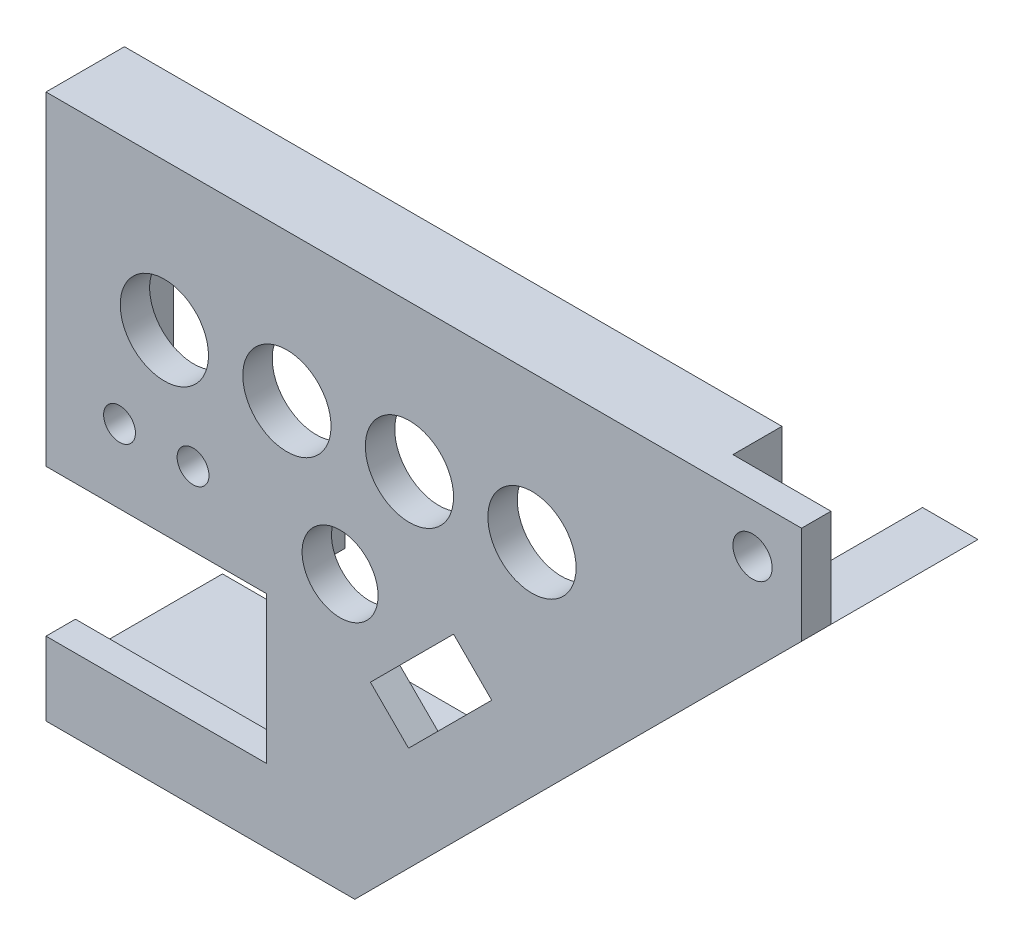
SolidWorks part; units mm, degrees
ref_plane "Plan de face" through (0, 0, 0) normal (0, 0, 1) x (1, 0, 0)
ref_plane "Plan de dessus" through (0, 0, 0) normal (0, 1, 0) x (1, 0, 0)
ref_plane "Plan de droite" through (0, 0, 0) normal (1, 0, 0) x (0, 0, -1)
sketch "Esquisse1" plane through (0, 0, 0) normal (0, 0, 1) x (1, 0, 0)
  line L0 (0, 0) -> (63, 0)
  line L1 (63, 0) -> (154.15, 91.15)
  line L2 (154.15, 91.15) -> (154.15, 111.15)
  line L3 (0, 111.15) -> (0, 0)
  line L4 (154.15, 111.15) -> (0, 111.15)
  dimension "D1" = 135
  dimension "D2" = 154.15
  dimension "D3" = 63
  dimension "D4" = 20
  dimension "D5" = 128.9056
extrude "Boss.-Extru.1" add sketch "Esquisse1" along normal blind 6
sketch "Esquisse2" plane through (0, 0, 6) normal (0, 0, 1) x (1, 0, 0)
  line L0 (0, 0) -> (63, 0) construction
  line L2 (154.15, 91.15) -> (154.15, 111.15) construction
  line L3 (66.1881, 39.9576) -> (73.9662, 32.1794)
  line L4 (73.9662, 32.1794) -> (90.9368, 49.15)
  line L5 (90.9368, 49.15) -> (83.1586, 56.9282)
  line L6 (83.1586, 56.9282) -> (66.1881, 39.9576)
  line L7 (63, 0) -> (154.15, 91.15) construction
  line L9 (154.15, 111.15) -> (0, 111.15) construction
  line L10 (0, 111.15) -> (0, 0) construction
  line L11 (0, 111.15) -> (0, 0) construction
  circle A0 centre (49.15, 81.15) radius 9
  circle A1 centre (74.15, 81.15) radius 9
  circle A2 centre (99.15, 81.15) radius 9
  circle A3 centre (24.15, 81.15) radius 9
  circle A4 centre (60, 56) radius 7.75
  circle A5 centre (30, 60) radius 3.25
  circle A6 centre (15, 60) radius 3.25
  point P14 (154.15, 101.15)
  point P31 (15, 50)
  point P32 (0, 0)
  dimension "D1" = 18
  dimension "D4" = 25
  dimension "D11" = 15.5
  dimension "D5" = 6.5
  dimension "D2" = 25
  dimension "D3" = 25
  dimension "D6" = 55
  dimension "D7" = 11
  dimension "D8" = 24
  dimension "D9" = 15
  dimension "D10" = 62
  dimension "D12" = 56
  dimension "D13" = 60
  dimension "D14" = 30
  dimension "D15" = 30
  dimension "D16" = 60
  dimension "D17" = 15
extrude "Enlèv. mat.-Extru.1" cut sketch "Esquisse2" against normal through all
sketch "Esquisse3" plane through (0, 0, 6) normal (0, 0, 1) x (1, 0, 0)
  line L0 (0, 111.15) -> (0, 0) construction
  line L1 (0, 45) -> (45, 45)
  line L2 (0, 45) -> (0, 15)
  line L3 (0, 15) -> (45, 15)
  line L4 (45, 45) -> (45, 15)
  line L5 (0, 0) -> (63, 0) construction
  dimension "D1" = 45
  dimension "D2" = 45
  dimension "D3" = 30
extrude "Enlèv. mat.-Extru.2" cut sketch "Esquisse3" against normal through all
sketch "Esquisse6" plane through (0, 0, 0) normal (0, 0, -1) x (-1, 0, 0)
  line L0 (-154.15, 91.15) -> (-142.8363, 91.15)
  line L1 (-142.8363, 91.15) -> (-59.6863, 8)
  line L2 (-59.6863, 8) -> (0, 8)
  line L3 (0, 15) -> (0, 0) construction
  line L4 (0, 8) -> (0, 0)
  line L5 (0, 0) -> (-63, 0)
  line L6 (-63, 0) -> (-154.15, 91.15) construction
  line L7 (0, 0) -> (-63, 0) construction
  line L8 (-63, 0) -> (-154.15, 91.15)
  dimension "D1" = 8
  dimension "D2" = 8
extrude "Boss.-Extru.2" add sketch "Esquisse6" along normal blind 30
sketch "Esquisse7" plane through (0, 0, 0) normal (0, 0, -1) x (-1, 0, 0)
  line L0 (-10, 55) -> (-45, 55)
  line L2 (-10, 55) -> (-10, 105.15)
  line L3 (-10, 105.15) -> (-128.15, 105.15)
  line L4 (-134.15, 111.15) -> (0, 111.15)
  line L5 (-154.15, 111.15) -> (0, 111.15) construction
  line L6 (0, 111.15) -> (0, 45)
  line L7 (-128.15, 76.4637) -> (-142.8363, 91.15)
  line L8 (-59.6863, 8) -> (-142.8363, 91.15) construction
  line L9 (-59.6863, 8) -> (-142.8363, 91.15) construction
  line L10 (-142.8363, 91.15) -> (-134.15, 91.15)
  line L11 (-128.15, 105.15) -> (-128.15, 76.4637)
  line L13 (-134.15, 91.15) -> (-134.15, 111.15)
  line L14 (-45, 55) -> (-45, 45)
  line L15 (-45, 45) -> (0, 45)
  line L16 (-45, 15) -> (-45, 45) construction
  dimension "D1" = 6
  dimension "D2" = 10
  dimension "D3" = 20
  dimension "D4" = 6
  dimension "D5" = 10
extrude "Boss.-Extru.3" add sketch "Esquisse7" along normal blind 10
sketch "Esquisse8" plane through (0, 0, 6) normal (0, 0, 1) x (1, 0, 0)
  line L0 (154.15, 91.15) -> (154.15, 111.15) construction
  line L1 (154.15, 111.15) -> (0, 111.15) construction
  circle A0 centre (144.15, 101.15) radius 4
  point P4 (0, 0)
  point P5 (0, 0)
  point P8 (149.8404, 102.8996)
  dimension "D3" = 8
  dimension "D1" = 10
  dimension "D2" = 10
extrude "Enlèv. mat.-Extru.3" cut sketch "Esquisse8" against normal through all
sketch "Esquisse9" plane through (0, 0, 0) normal (-1, 0, 0) x (0, 0, 1)
  line L0 (-10, 45) -> (-10, 111.15) construction
  line L1 (6, 111.15) -> (-10, 111.15) construction
  circle A0 centre (-5, 101.15) radius 1.35
  point P4 (0, 0)
  point P6 (-4.8474, 99.2407)
  dimension "D1" = 2.7
  dimension "D2" = 5
  dimension "D3" = 10
extrude "Enlèv. mat.-Extru.4" cut sketch "Esquisse9" against normal up to next
pattern_linear "Répétition linéaire1" count 3 spacing 20 along (0, -1, 0) of "Enlèv. mat.-Extru.4"
sketch "Esquisse10" plane through (0, 0, 0) normal (-1, 0, 0) x (0, 0, 1)
  line L0 (6, 111.15) -> (-10, 111.15) construction
  line L1 (6, 111.15) -> (6, 45) construction
  line L2 (6, 0) -> (-30, 0) construction
  line L3 (6, 15) -> (6, 0) construction
  line L4 (0, 15) -> (0, 8) construction
  circle A0 centre (0, 91.15) radius 3
  circle A1 centre (0, 71.15) radius 3
  circle A2 centre (0, 51.15) radius 3
  circle A3 centre (-14, 4) radius 3
  circle A4 centre (0, 4) radius 3
  point P16 (0, 0)
  point P19 (0, 0)
  dimension "D2" = 6
  dimension "D1" = 20
  dimension "D3" = 20
  dimension "D4" = 20
  dimension "D5" = 6
  dimension "D6" = 4
  dimension "D8" = 20
extrude "Enlèv. mat.-Extru.5" cut sketch "Esquisse10" against normal up to surface (10 mm away) up to face at (10, 79.8, -5)
sketch "Esquisse11" plane through (0, 0, 0) normal (0, -1, 0) x (1, 0, 0)
  line L0 (63, 6) -> (63, -30) construction
  line L1 (0, -30) -> (63, -30)
  line L2 (0, -30) -> (0, -20)
  line L3 (0, -20) -> (63, -20)
  line L4 (63, -30) -> (63, -20)
  dimension "D1" = 10
extrude "Enlèv. mat.-Extru.6" cut sketch "Esquisse11" against normal blind 5
sketch "Esquisse12" plane through (31.5, -31.5, 0) normal (0.7071, -0.7071, 0) x (0, 0, -1)
  line L0 (30, 173.4533) -> (30, 44.5477) construction
  line L1 (20, 65.5005) -> (30, 65.5005)
  line L2 (20, 65.5005) -> (20, 152.5005)
  line L3 (20, 152.5005) -> (30, 152.5005)
  line L4 (30, 65.5005) -> (30, 152.5005)
  point P6 (30, 109.0005)
  point P7 (30, 109.0005)
  dimension "D1" = 10
  dimension "D2" = 87
extrude "Enlèv. mat.-Extru.7" cut sketch "Esquisse12" against normal blind 5
